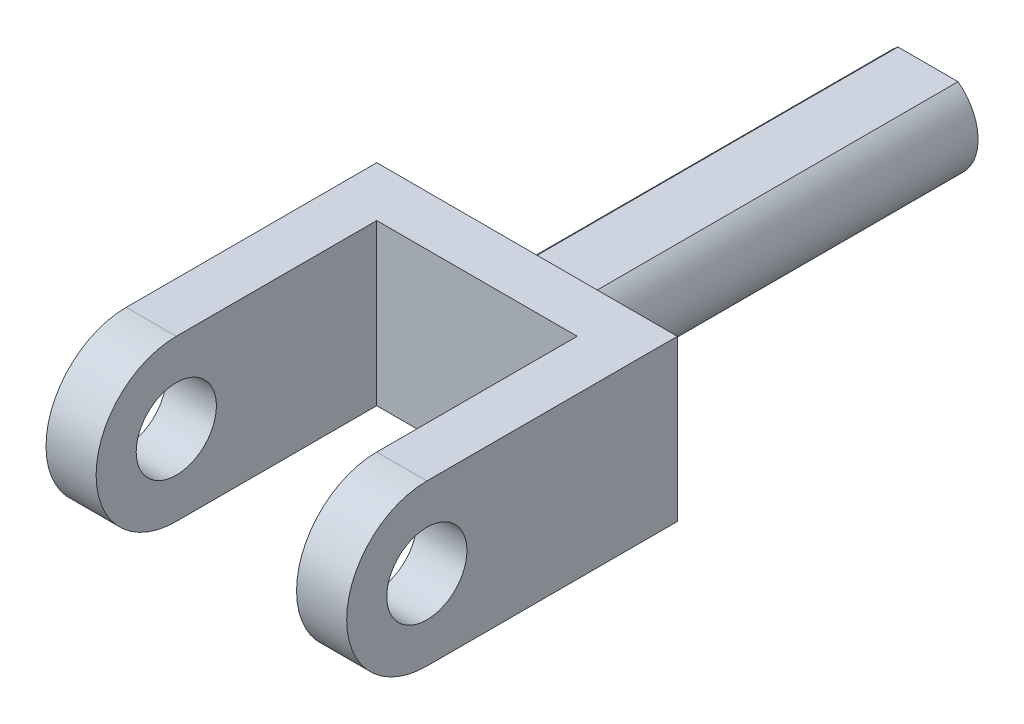
SolidWorks part; units mm, degrees
material "1060 合金"
ref_plane "前视基准面" through (0, 0, 0) normal (0, 0, 1) x (1, 0, 0)
ref_plane "上视基准面" through (0, 0, 0) normal (0, 1, 0) x (1, 0, 0)
ref_plane "右视基准面" through (0, 0, 0) normal (1, 0, 0) x (0, 0, -1)
sketch "草图2" plane through (0, 0, 0) normal (1, 0, 0) x (0, 0, -1)
  line L1 (-25, -8) -> (0, -8)
  line L3 (-25, 8) -> (0, 8)
  line L4 (0, -8) -> (0, 8)
  circle A0 centre (-25, 0) radius 4
  arc A1 (-25, 8) -> (-25, -8) centre (-25, 0) ccw
  point P2 (0, 0)
  dimension "D2" = 8
  dimension "D3" = 16
  dimension "D1" = 25
extrude "凸台-拉伸1" add sketch "草图2" along normal mid plane 30
sketch "草图3" plane through (0, 0, 0) normal (0, 1, 0) x (1, 0, 0)
  line L0 (-15, -33) -> (15, -33) construction
  line L1 (-10, -33) -> (10, -33)
  line L2 (-10, -33) -> (-10, -5)
  line L3 (-10, -5) -> (10, -5)
  line L4 (10, -33) -> (10, -5)
  point P6 (0, -5)
  dimension "D1" = 20
  dimension "D2" = 28
extrude "切除-拉伸1" cut sketch "草图3" against normal through all both and the other way through all
sketch "草图4" plane through (0, 0, 0) normal (0, 0, -1) x (-1, 0, 0)
  line L0 (-8.78, 0) -> (8.78, 0) construction
  line L3 (-3, -4) -> (3, -4)
  line L4 (-3, 4) -> (3, 4)
  arc A0 (3, -4) -> (3, 4) centre (0, 0) ccw
  arc A1 (-3, 4) -> (-3, -4) centre (0, 0) ccw
  point P13 (0, 0)
  dimension "D1" = 10
  dimension "D2" = 4
extrude "凸台-拉伸2" add sketch "草图4" along normal blind 40
